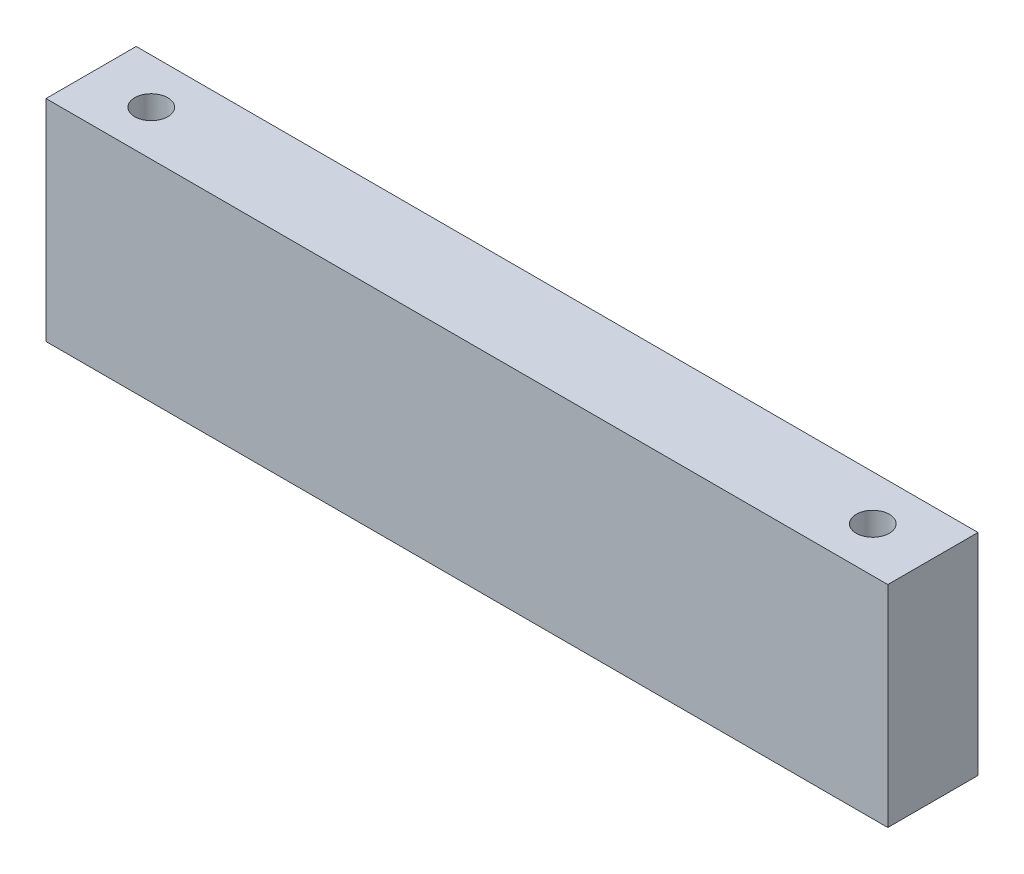
SolidWorks part; units mm, degrees
ref_plane "Front Plane" through (0, 0, 0) normal (0, 0, 1) x (1, 0, 0)
ref_plane "Top Plane" through (0, 0, 0) normal (0, 1, 0) x (1, 0, 0)
ref_plane "Right Plane" through (0, 0, 0) normal (1, 0, 0) x (0, 0, -1)
sketch "Sketch1" plane through (0, 0, 0) normal (0, 0, 1) x (1, 0, 0)
  line L1 (-140, -35) -> (140, -35)
  line L2 (-140, -35) -> (-140, 35)
  line L3 (-140, 35) -> (140, 35)
  line L4 (140, -35) -> (140, 35)
  point P0 (0, 0)
extrude "Boss-Extrude1" add sketch "Sketch1" along normal blind 30
sketch "Sketch2" plane through (0, 35, 0) normal (0, 1, 0) x (1, 0, 0)
  line L0 (-140, -30) -> (-120, -30)
  line L1 (140, -30) -> (-140, -30) construction
  circle A0 centre (-120, -15) radius 5.5
  circle A1 centre (120, -15) radius 5.5
  dimension "D1" = 2
extrude "Cut-Extrude1" cut sketch "Sketch2" against normal blind 80 contours A0 | A1
